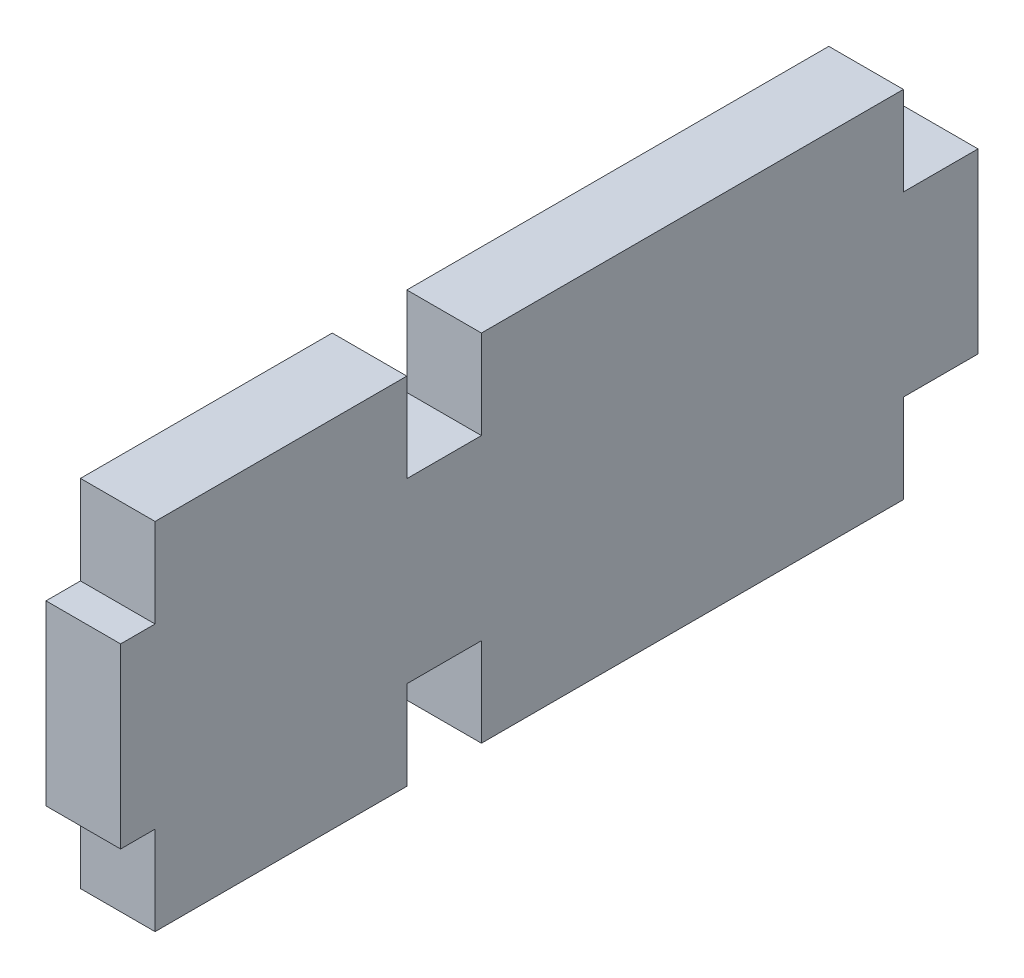
SolidWorks part; units mm, degrees
ref_plane "Front Plane" through (0, 0, 0) normal (0, 0, 1) x (1, 0, 0)
ref_plane "Top Plane" through (0, 0, 0) normal (0, 1, 0) x (1, 0, 0)
ref_plane "Right Plane" through (0, 0, 0) normal (1, 0, 0) x (0, 0, -1)
sketch "Sketch1" plane through (0, 0, 0) normal (1, 0, 0) x (0, 0, -1)
  line L1 (0, 0) -> (61.3, 0)
  line L2 (0, 0) -> (0, 25.4)
  line L3 (0, 25.4) -> (61.3, 25.4)
  line L4 (61.3, 0) -> (61.3, 25.4)
  dimension "D1" = 61.3
  dimension "D2" = 25.4
extrude "Boss-Extrude1" add sketch "Sketch1" along normal blind 5.334
sketch "Sketch2" plane through (5.334, 0, 0) normal (1, 0, 0) x (0, 0, -1)
  line L0 (61.3, 25.4) -> (0, 25.4) construction
  line L1 (0, 25.4) -> (2.4638, 25.4)
  line L2 (0, 25.4) -> (0, 19.05)
  line L3 (0, 19.05) -> (2.4638, 19.05)
  line L4 (2.4638, 25.4) -> (2.4638, 19.05)
  line L5 (0, 0) -> (2.4638, 0)
  line L6 (0, 0) -> (0, 6.35)
  line L7 (0, 6.35) -> (2.4638, 6.35)
  line L8 (2.4638, 0) -> (2.4638, 6.35)
  line L9 (20.4638, 25.4) -> (25.7978, 25.4)
  line L10 (20.4638, 25.4) -> (20.4638, 19.05)
  line L11 (20.4638, 19.05) -> (25.7978, 19.05)
  line L12 (25.7978, 25.4) -> (25.7978, 19.05)
  line L13 (0, 0) -> (61.3, 0) construction
  line L14 (20.4638, 0) -> (25.7978, 0)
  line L15 (20.4638, 0) -> (20.4638, 6.35)
  line L16 (20.4638, 6.35) -> (25.7978, 6.35)
  line L17 (25.7978, 0) -> (25.7978, 6.35)
  line L18 (2.4638, 19.05) -> (2.4638, 6.35) construction
  line L19 (61.3, 0) -> (55.966, 0)
  line L20 (61.3, 0) -> (61.3, 6.35)
  line L21 (61.3, 6.35) -> (55.966, 6.35)
  line L22 (55.966, 0) -> (55.966, 6.35)
  line L23 (61.3, 25.4) -> (55.966, 25.4)
  line L24 (61.3, 25.4) -> (61.3, 19.05)
  line L25 (61.3, 19.05) -> (55.966, 19.05)
  line L26 (55.966, 25.4) -> (55.966, 19.05)
  dimension "D1" = 12.7
  dimension "D2" = 18
  dimension "D3" = 2.4638
  dimension "D4" = 5.334
extrude "Cut-Extrude1" cut sketch "Sketch2" against normal through all
equation "\"material\"= \"gmaterial@base.assembly\""
equation "\"D1@Boss-Extrude1\"=\"material\""
equation "\"D3@Sketch2\"=\"acrylic_sm@base.assembly\""
equation "\"D4@Sketch2\"=\"material\""
